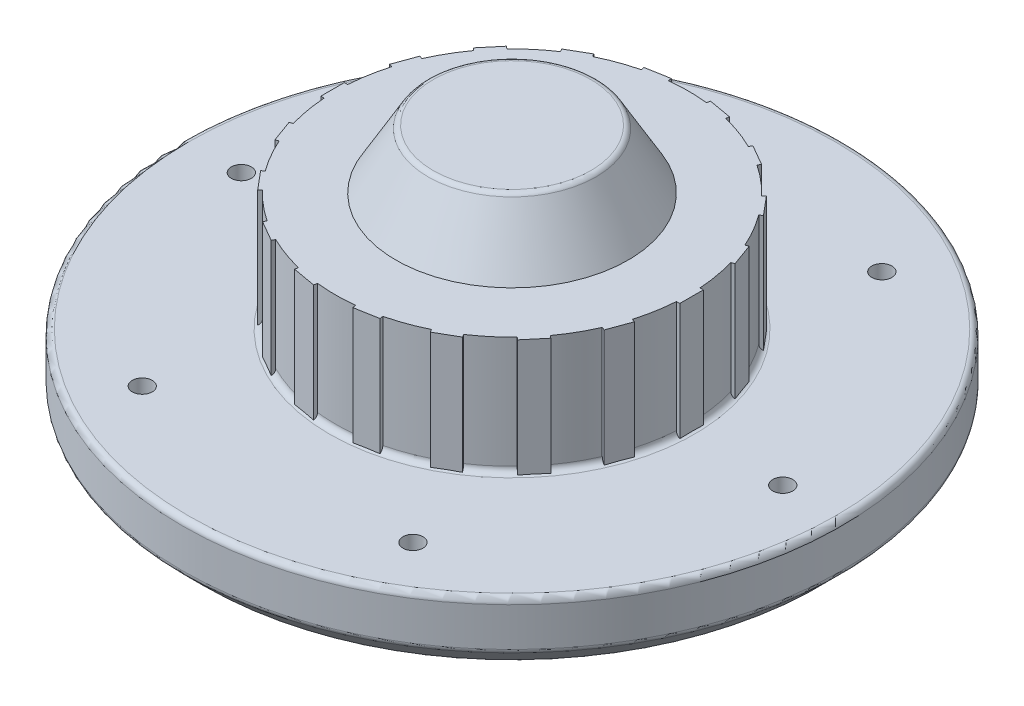
SolidWorks part; units mm, degrees
material "PET"
ref_plane "Front Plane" through (0, 0, 0) normal (0, 0, 1) x (1, 0, 0)
ref_plane "Top Plane" through (0, 0, 0) normal (0, 1, 0) x (1, 0, 0)
ref_plane "Right Plane" through (0, 0, 0) normal (1, 0, 0) x (0, 0, -1)
sketch "Sketch1" plane through (0, 0, 0) normal (0, 0, 1) x (1, 0, 0)
  line L0 (0, 0) -> (0, 42) construction
  line L1 (0, 42) -> (13.9765, 42)
  line L2 (13.9765, 42) -> (19.75, 32)
  line L3 (19.75, 32) -> (30, 32)
  line L4 (30, 32) -> (30, 12)
  line L5 (56, 12) -> (56, 4)
  line L6 (56, 4) -> (52, 0)
  line L7 (52, 0) -> (0, 0)
  line L8 (0, 0) -> (0, 42)
  line L9 (30, 12) -> (56, 12)
  dimension "D1" = 39.5
  dimension "D3" = 60
  dimension "D5" = 10
  dimension "D6" = 4
  dimension "D7" = 4
  dimension "D2" = 56
  dimension "D4" = 30
  dimension "D8" = 20
  dimension "D9" = 12
revolve "body" add sketch "Sketch1" angle 360 about L0
sketch "Sketch3" plane through (0, 0, 0) normal (0, -1, 0) x (1, 0, 0)
  point P0 (46, 0)
  dimension "D1" = 46
hole_wizard "socket_hole" positions "Sketch3" profile "Sketch4" counterbore size "M3" standard "DIN" end condition up to next
sketch "Sketch4" plane through (46, 0, 0) normal (1, 0, 0) x (0, 0, -1)
  line L0 (0, 0) -> (0, 12)
  line L1 (0, 12) -> (1.7, 12)
  line L3 (1.7, 12) -> (1.7, 8)
  line L4 (1.7, 8) -> (3.25, 8)
  line L5 (3.25, 8) -> (3.25, 0)
  line L7 (3.25, 0) -> (0, 0)
  line L11 (0, -6.35) -> (0, 107.95) construction
  dimension "Thru Hole Dia." = 3.4
  dimension "Thru Hole Depth" = 12
  dimension "C'Bore Dia." = 6.5
  dimension "C'Bore Depth" = 8
pattern_circular "socket_hole_pattern" count 6 over 360 about axis through (0, 0, 0) along (0, 1, 0) of "socket_hole"
fillet "overall_fillets" radius 1 11 edges at (23, 0, 36.5872) (46, 0, -3.25) (23, 0, -43.0872) (-23, 0, -43.0872) (-46, 0, -3.25) (-23, 0, 36.5872) (0, 4, -56) (0, 0, -52) (0, 42, -13.9765) (0, 12, -30) (0, 12, -56)
sketch "Sketch6" plane through (0, 32, 0) normal (0, 1, 0) x (1, 0, 0)
  line L1 (29.5, -2) -> (30.5, -2)
  line L2 (29.5, -2) -> (29.5, 2)
  line L3 (29.5, 2) -> (30.5, 2)
  line L4 (30.5, -2) -> (30.5, 2)
  line L5 (29.5, -2) -> (30.5, 2) construction
  line L6 (29.5, 2) -> (30.5, -2) construction
  circle A0 centre (0, 0) radius 30 construction
  point P0 (30, 0)
  point P7 (0, 0)
  dimension "D1" = 1
  dimension "D2" = 4
extrude "side_extrusion" add sketch "Sketch6" against normal up to next
pattern_circular "CirPattern1" count 18 over 360 about axis through (0, 0, 0) along (0, 1, 0) of "side_extrusion"
equation "\"paper_size\" = 600mm"
equation "\"cb_roll_d_outer\" = 86mm"
equation "\"cb_roll_d_inner\" = 76mm"
equation "\"attached_len\" = \"spring_l_max\" * 2 - \"spring_l_min\" + 18"
equation "\"helper_d\" = 92mm"
equation "\"outer_d\" = 112mm"
equation "\"spring_l_max\" = 25mm"
equation "\"spring_l_min\" = 10mm"
equation "\"cone_d_larger\" = 40mm"
equation "\"cone_angle\" = 60deg"
equation "\"D1@Sketch1\"=\"cone_d_larger\" - 0.5"
equation "\"D3@Sketch1\"=\"cone_angle\""
equation "\"D2@Sketch1\"=\"outer_d\" / 2"
equation "\"bottom_screw_ring_d\" = 92mm"
equation "\"D1@Sketch3\"=\"bottom_screw_ring_d\" / 2"
